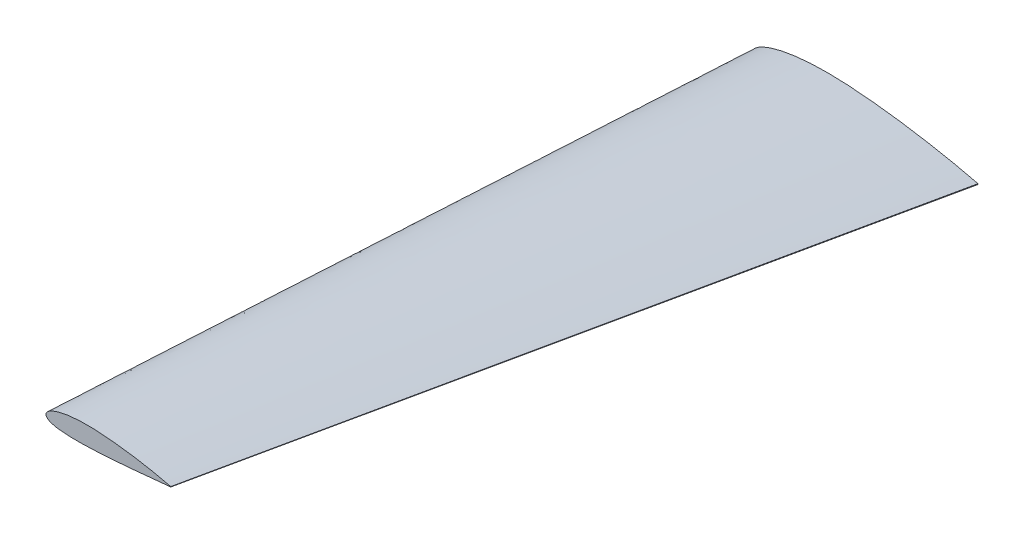
SolidWorks part; units mm, degrees
ref_plane "Front Plane" through (0, 0, 0) normal (0, 0, 1) x (1, 0, 0)
ref_plane "Top Plane" through (0, 0, 0) normal (0, 1, 0) x (1, 0, 0)
ref_plane "Right Plane" through (0, 0, 0) normal (1, 0, 0) x (0, 0, -1)
sketch "1st airfoil" plane through (0, 0, 0) normal (0, 0, 1) x (1, 0, 0)
  line L0 (1125.6, -0.9091) -> (1125.6, -4.4431)
  line L1 (1125.6, -2.6761) -> (0, 0) construction
  spline S1 degree 3 poles (1125.6, -0.9091) (1124.6249, -0.6601) (1120.6206, 0.3624) (1111.5693, 2.5059) (1096.5502, 6.1224) (1075.7214, 10.965) (1049.3095, 16.9393) (1017.5898, 23.8766) (980.8794, 31.5235) (939.5759, 39.7382) (894.1063, 48.2538) (844.962, 56.8832) (792.6632, 65.3821) (737.7799, 73.552) (680.9102, 81.1661) (622.6798, 88.0047) (563.7284, 93.8874) (504.6924, 98.5611) (446.0632, 101.9611) (388.4791, 103.5494) (332.6356, 103.1133) (279.3663, 100.6265) (229.313, 96.1664) (183.0648, 89.8031) (141.1558, 81.7693) (104.0686, 72.2412) (72.1819, 61.5585) (45.8293, 49.9396) (25.1736, 37.6902) (10.3088, 24.9453) (1.2227, 11.4916) (-1.0222, -2.7924) (4.0079, -16.3152) (15.4089, -27.7408) (32.1879, -37.4496) (54.3092, -45.7879) (81.6387, -52.7672) (113.9385, -58.3663) (150.8843, -62.5416) (192.0961, -65.3344) (237.1526, -66.7933) (285.608, -67.0342) (336.9779, -66.1941) (390.754, -64.458) (446.579, -62.0682) (503.8906, -59.0873) (562.0748, -55.3455) (620.3342, -51.1258) (678.0303, -46.5686) (734.5328, -41.8308) (789.2271, -37.0832) (841.5061, -32.3604) (890.7944, -27.8136) (936.54, -23.4833) (978.2267, -19.457) (1015.3792, -15.8099) (1047.574, -12.5678) (1074.4416, -9.8101) (1095.6746, -7.5986) (1111.019, -5.9939) (1120.3356, -4.9897) (1124.5195, -4.5553) (1125.6, -4.4431) knots 0 0 0 0 0.001303 0.005353 0.012046 0.021311 0.033048 0.047117 0.063363 0.081612 0.101657 0.123274 0.146233 0.170278 0.195136 0.22054 0.246208 0.27186 0.297234 0.32226 0.346453 0.369544 0.391307 0.411513 0.42998 0.446543 0.46107 0.473486 0.48378 0.492064 0.498682 0.504377 0.51007 0.516665 0.524878 0.535025 0.54719 0.56136 0.577449 0.595324 0.614843 0.635824 0.658075 0.681379 0.705505 0.73044 0.755703 0.781015 0.806091 0.83066 0.85445 0.877193 0.898643 0.918556 0.936704 0.952884 0.966904 0.978612 0.987864 0.994552 0.998593 1 1 1 1
  dimension "D1" = 1125.6
ref_plane "Plane3" through (3643.731, 0, 0) normal (1, 0, 0) x (0, 0, -1)
ref_plane "Plane4" through (0, 0, 3643.731) normal (0, 0, 1) x (1, 0, 0)
sketch "Sketch5" plane through (0, 0, 3643.731) normal (0, 0, 1) x (1, 0, 0)
  line L0 (745.178, 323.0739) -> (745.178, 321.1206)
  line L1 (745.178, 322.0973) -> (123.044, 323.5764) construction
  spline S0 degree 3 poles (745.178, 323.0739) (744.6391, 323.2115) (742.4258, 323.7767) (737.4231, 324.9614) (729.1218, 326.9603) (717.6095, 329.6369) (703.0113, 332.939) (685.4794, 336.7733) (665.1891, 340.9998) (642.36, 345.5402) (617.2284, 350.2469) (590.0657, 355.0165) (561.1595, 359.7139) (530.8247, 364.2296) (499.3921, 368.438) (467.2074, 372.2177) (434.6242, 375.4692) (401.9942, 378.0524) (369.5891, 379.9316) (337.7616, 380.8095) (306.8961, 380.5685) (277.4535, 379.194) (249.7883, 376.7288) (224.2263, 373.2118) (201.0627, 368.7713) (180.5641, 363.505) (162.9399, 357.6006) (148.3745, 351.1786) (136.9578, 344.4083) (128.7418, 337.364) (123.7199, 329.928) (122.4791, 322.033) (125.2593, 314.5588) (131.5607, 308.2437) (140.8347, 302.8775) (153.0615, 298.2688) (168.1668, 294.4112) (186.0193, 291.3165) (206.4398, 289.0088) (229.2181, 287.4652) (254.1214, 286.6588) (280.9033, 286.5257) (309.2962, 286.99) (339.0189, 287.9496) (369.8741, 289.2705) (401.551, 290.9181) (433.7102, 292.9862) (465.911, 295.3185) (497.8003, 297.8373) (529.03, 300.456) (559.2603, 303.08) (588.1556, 305.6904) (615.3979, 308.2035) (640.6821, 310.5968) (663.7228, 312.8222) (684.2575, 314.838) (702.0521, 316.63) (716.9021, 318.1542) (728.6379, 319.3765) (737.1189, 320.2634) (742.2684, 320.8185) (744.5808, 321.0586) (745.178, 321.1206) knots 0 0 0 0 0.001303 0.005353 0.012046 0.021311 0.033048 0.047117 0.063363 0.081612 0.101657 0.123274 0.146233 0.170278 0.195136 0.22054 0.246208 0.27186 0.297234 0.32226 0.346453 0.369544 0.391307 0.411513 0.42998 0.446543 0.46107 0.473486 0.48378 0.492064 0.498682 0.504377 0.51007 0.516665 0.524878 0.535025 0.54719 0.56136 0.577449 0.595324 0.614843 0.635824 0.658075 0.681379 0.705505 0.73044 0.755703 0.781015 0.806091 0.83066 0.85445 0.877193 0.898643 0.918556 0.936704 0.952884 0.966904 0.978612 0.987864 0.994552 0.998593 1 1 1 1
sketch3d "3DSketch5"
  line L0 (745.178, 322.0973, 3643.731) -> (1125.6, -2.6761, 0)
  line L1 (745.178, 322.0973, 3643.731) -> (123.044, 323.5764, 3643.731) construction
  line L2 (1125.6, -0.9091, 0) -> (1125.6, -4.4431, 0) construction
  line L3 (123.044, 323.5764, 3643.731) -> (0, 0, 0)
  line L4 (1125.6, -2.6761, 0) -> (0, 0, 0) construction
  spline S0 degree 3 poles (745.178, 323.0739, 3643.731) (744.6391, 323.2115, 3643.731) (742.4258, 323.7767, 3643.731) (737.4231, 324.9614, 3643.731) (729.1218, 326.9603, 3643.731) (717.6095, 329.6369, 3643.731) (703.0113, 332.939, 3643.731) (685.4794, 336.7733, 3643.731) (665.1891, 340.9998, 3643.731) (642.36, 345.5402, 3643.731) (617.2284, 350.2469, 3643.731) (590.0657, 355.0165, 3643.731) (561.1595, 359.7139, 3643.731) (530.8247, 364.2296, 3643.731) (499.3921, 368.438, 3643.731) (467.2074, 372.2177, 3643.731) (434.6242, 375.4692, 3643.731) (401.9942, 378.0524, 3643.731) (369.5891, 379.9316, 3643.731) (337.7616, 380.8095, 3643.731) (306.8961, 380.5685, 3643.731) (277.4535, 379.194, 3643.731) (249.7883, 376.7288, 3643.731) (224.2263, 373.2118, 3643.731) (201.0627, 368.7713, 3643.731) (180.5641, 363.505, 3643.731) (162.9399, 357.6006, 3643.731) (148.3745, 351.1786, 3643.731) (136.9578, 344.4083, 3643.731) (128.7418, 337.364, 3643.731) (123.7199, 329.928, 3643.731) (122.4791, 322.033, 3643.731) (125.2593, 314.5588, 3643.731) (131.5607, 308.2437, 3643.731) (140.8347, 302.8775, 3643.731) (153.0615, 298.2688, 3643.731) (168.1668, 294.4112, 3643.731) (186.0193, 291.3165, 3643.731) (206.4398, 289.0088, 3643.731) (229.2181, 287.4652, 3643.731) (254.1214, 286.6588, 3643.731) (280.9033, 286.5257, 3643.731) (309.2962, 286.99, 3643.731) (339.0189, 287.9496, 3643.731) (369.8741, 289.2705, 3643.731) (401.551, 290.9181, 3643.731) (433.7102, 292.9862, 3643.731) (465.911, 295.3185, 3643.731) (497.8003, 297.8373, 3643.731) (529.03, 300.456, 3643.731) (559.2603, 303.08, 3643.731) (588.1556, 305.6904, 3643.731) (615.3979, 308.2035, 3643.731) (640.6821, 310.5968, 3643.731) (663.7228, 312.8222, 3643.731) (684.2575, 314.838, 3643.731) (702.0521, 316.63, 3643.731) (716.9021, 318.1542, 3643.731) (728.6379, 319.3765, 3643.731) (737.1189, 320.2634, 3643.731) (742.2684, 320.8185, 3643.731) (744.5808, 321.0586, 3643.731) (745.178, 321.1206, 3643.731) knots 0 0 0 0 0.001303 0.005353 0.012046 0.021311 0.033048 0.047117 0.063363 0.081612 0.101657 0.123274 0.146233 0.170278 0.195136 0.22054 0.246208 0.27186 0.297234 0.32226 0.346453 0.369544 0.391307 0.411513 0.42998 0.446543 0.46107 0.473486 0.48378 0.492064 0.498682 0.504377 0.51007 0.516665 0.524878 0.535025 0.54719 0.56136 0.577449 0.595324 0.614843 0.635824 0.658075 0.681379 0.705505 0.73044 0.755703 0.781015 0.806091 0.83066 0.85445 0.877193 0.898643 0.918556 0.936704 0.952884 0.966904 0.978612 0.987864 0.994552 0.998593 1 1 1 1 construction
  spline S1 degree 3 poles (1125.6, -0.9091, 0) (1124.6249, -0.6601, 0) (1120.6206, 0.3624, 0) (1111.5693, 2.5059, 0) (1096.5502, 6.1224, 0) (1075.7214, 10.965, 0) (1049.3095, 16.9393, 0) (1017.5898, 23.8766, 0) (980.8794, 31.5235, 0) (939.5759, 39.7382, 0) (894.1063, 48.2538, 0) (844.962, 56.8832, 0) (792.6632, 65.3821, 0) (737.7799, 73.552, 0) (680.9102, 81.1661, 0) (622.6798, 88.0047, 0) (563.7284, 93.8874, 0) (504.6924, 98.5611, 0) (446.0632, 101.9611, 0) (388.4791, 103.5494, 0) (332.6356, 103.1133, 0) (279.3663, 100.6265, 0) (229.313, 96.1664, 0) (183.0648, 89.8031, 0) (141.1558, 81.7693, 0) (104.0686, 72.2412, 0) (72.1819, 61.5585, 0) (45.8293, 49.9396, 0) (25.1736, 37.6902, 0) (10.3088, 24.9453, 0) (1.2227, 11.4916, 0) (-1.0222, -2.7924, 0) (4.0079, -16.3152, 0) (15.4089, -27.7408, 0) (32.1879, -37.4496, 0) (54.3092, -45.7879, 0) (81.6387, -52.7672, 0) (113.9385, -58.3663, 0) (150.8843, -62.5416, 0) (192.0961, -65.3344, 0) (237.1526, -66.7933, 0) (285.608, -67.0342, 0) (336.9779, -66.1941, 0) (390.754, -64.458, 0) (446.579, -62.0682, 0) (503.8906, -59.0873, 0) (562.0748, -55.3455, 0) (620.3342, -51.1258, 0) (678.0303, -46.5686, 0) (734.5328, -41.8308, 0) (789.2271, -37.0832, 0) (841.5061, -32.3604, 0) (890.7944, -27.8136, 0) (936.54, -23.4833, 0) (978.2267, -19.457, 0) (1015.3792, -15.8099, 0) (1047.574, -12.5678, 0) (1074.4416, -9.8101, 0) (1095.6746, -7.5986, 0) (1111.019, -5.9939, 0) (1120.3356, -4.9897, 0) (1124.5195, -4.5553, 0) (1125.6, -4.4431, 0) knots 0 0 0 0 0.001303 0.005353 0.012046 0.021311 0.033048 0.047117 0.063363 0.081612 0.101657 0.123274 0.146233 0.170278 0.195136 0.22054 0.246208 0.27186 0.297234 0.32226 0.346453 0.369544 0.391307 0.411513 0.42998 0.446543 0.46107 0.473486 0.48378 0.492064 0.498682 0.504377 0.51007 0.516665 0.524878 0.535025 0.54719 0.56136 0.577449 0.595324 0.614843 0.635824 0.658075 0.681379 0.705505 0.73044 0.755703 0.781015 0.806091 0.83066 0.85445 0.877193 0.898643 0.918556 0.936704 0.952884 0.966904 0.978612 0.987864 0.994552 0.998593 1 1 1 1 construction
loft "Loft2" add profiles "1st airfoil", "Sketch5"
